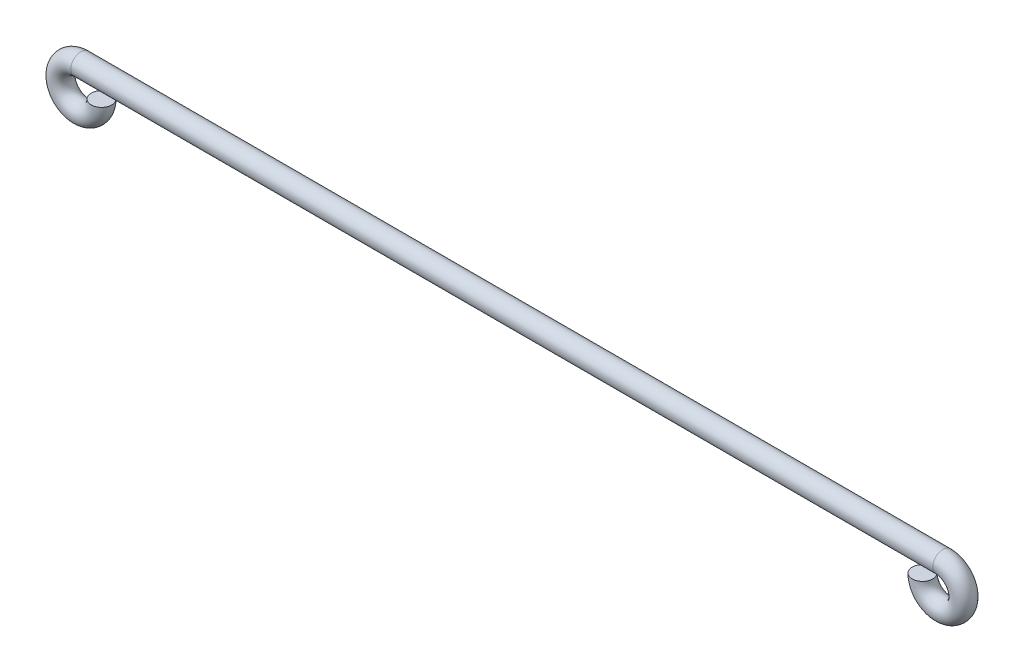
SolidWorks part; units mm, degrees
ref_plane "Plan de face" through (0, 0, 0) normal (0, 0, 1) x (1, 0, 0)
ref_plane "Plan de dessus" through (0, 0, 0) normal (0, 1, 0) x (1, 0, 0)
ref_plane "Plan de droite" through (0, 0, 0) normal (1, 0, 0) x (0, 0, -1)
sketch "Esquisse1" plane through (0, 0, 0) normal (0, 0, 1) x (1, 0, 0)
  line L0 (41, 1) -> (-1, 1)
  line L1 (-1, 0) -> (41, 0) construction
  line L2 (-2, 0.8138) -> (-2, -1.1803) construction
  line L3 (42, 0.8689) -> (42, -1.3516) construction
  line L4 (55, 0) -> (-55, 0) construction
  line L5 (0, -55) -> (0, 55) construction
  arc A0 (-1, 1) -> (0, 0) centre (-1, 0) ccw
  arc A1 (40, 0) -> (41, 1) centre (41, 0) ccw
  dimension "D1" = 2
  dimension "D2" = 2
  dimension "D3" = 44
sketch "Esquisse2" plane through (0, 0, 0) normal (0, 1, 0) x (1, 0, 0)
  circle A0 centre (0, 0) radius 0.5
  dimension "D1" = 1
sweep "Balayage1" add profiles "Esquisse2" path "Esquisse1"
